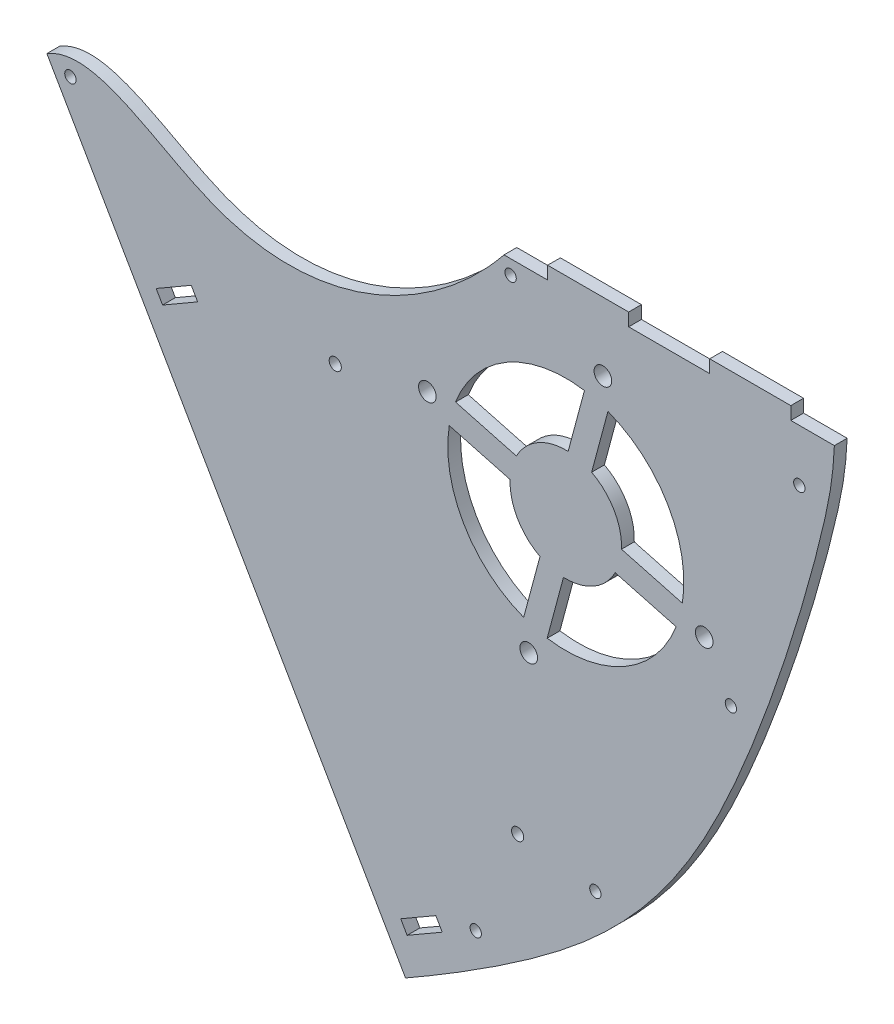
SolidWorks part; units mm, degrees
ref_plane "Front Plane" through (0, 0, 0) normal (0, 0, 1) x (1, 0, 0)
ref_plane "Top Plane" through (0, 0, 0) normal (0, 1, 0) x (1, 0, 0)
ref_plane "Right Plane" through (0, 0, 0) normal (1, 0, 0) x (0, 0, -1)
sketch "Sketch1" plane through (0, 0, 0) normal (0, 0, 1) x (1, 0, 0)
  line L0 (-241.6982, -23.3423) -> (-182.9843, -125.0377)
  line L1 (-213.036, -79.2761) -> (-94.3165, -10.7334) construction
  line L2 (-128.9095, -9.9573) -> (-47.4019, -9.9573)
  line L3 (-182.9843, -125.0377) -> (-153.2062, -176.6149)
  line L4 (-208.8162, -60.2955) -> (-150.0662, -162.0535) construction
  line L5 (-151.5313, -162.8993) -> (-146.1742, -159.8064) construction
  line L6 (-118.1557, -9.9573) -> (-98.1557, -9.9573)
  line L7 (-206.0711, -55.0502) -> (-214.7314, -60.0502)
  line L8 (-206.0711, -55.0502) -> (-204.4861, -57.7955)
  line L9 (-204.4861, -57.7955) -> (-213.1464, -62.7955)
  line L10 (-214.7314, -60.0502) -> (-213.1464, -62.7955)
  line L11 (-206.0711, -55.0502) -> (-213.1464, -62.7955) construction
  line L12 (-204.4861, -57.7955) -> (-214.7314, -60.0502) construction
  line L13 (-118.1557, -9.9573) -> (-118.1557, -6.7873)
  line L14 (-118.1557, -6.7873) -> (-98.1557, -6.7873)
  line L15 (-98.1557, -9.9573) -> (-98.1557, -6.7873)
  line L16 (-118.1557, -9.9573) -> (-98.1557, -6.7873) construction
  line L17 (-118.1557, -6.7873) -> (-98.1557, -9.9573) construction
  line L18 (-78.1557, -9.9573) -> (-58.1557, -9.9573)
  line L19 (-78.1557, -9.9573) -> (-78.1557, -6.7873)
  line L20 (-78.1557, -6.7873) -> (-58.1557, -6.7873)
  line L21 (-58.1557, -9.9573) -> (-58.1557, -6.7873)
  line L22 (-78.1557, -9.9573) -> (-58.1557, -6.7873) construction
  line L23 (-78.1557, -6.7873) -> (-58.1557, -9.9573) construction
  line L24 (-114.7432, -141.6597) -> (-155.5115, -165.1973) construction
  line L25 (-145.7361, -159.5535) -> (-152.8114, -167.2988) construction
  line L27 (-145.7361, -159.5535) -> (-154.3964, -164.5535)
  line L28 (-144.1511, -162.2988) -> (-152.8114, -167.2988)
  line L29 (-145.7361, -159.5535) -> (-144.1511, -162.2988)
  line L30 (-154.3964, -164.5535) -> (-152.8114, -167.2988)
  line L31 (-144.1511, -162.2988) -> (-154.3964, -164.5535) construction
  spline S0 degree 3 poles (-47.4019, -9.9573) (-47.8291, -14.2519) (-46.724, -19.9699) (-68.6824, -93.9596) (-98.4889, -144.1566) (-142.9712, -170.7541) (-153.2062, -176.6149) knots 0.137311 0.137311 0.137311 0.137311 0.404181 0.636361 0.837197 0.978117 0.978117 0.978117 0.978117
  spline S1 degree 3 poles (-241.6982, -23.3423) (-229.9179, -16.192) (-187.8178, -53.9735) (-145.5398, -30.6189) (-128.9095, -9.9573) knots 0 0 0 0 0.34889 1 1 1 1
  point P5 (-210.0721, -60.1842)
  point P18 (-209.6087, -58.9228)
  point P24 (-68.1557, -8.3723)
  point P27 (-108.1557, -8.3723)
  point P28 (-88.1557, -9.9573)
  point P38 (-149.7371, -164.6875)
  point P42 (-149.2737, -163.4261)
  dimension "D10" = 206.4057
  dimension "D1" = 3.17
  dimension "D2" = 10
  dimension "D3" = 10
  dimension "D4" = 10
  dimension "D5" = 20
  dimension "D6" = 3.17
  dimension "D7" = 5
  dimension "D8" = 3.17
  dimension "D9" = 10
extrude "Boss-Extrude1" add sketch "Sketch1" along normal blind 3.15 contours S1 L0 L3 S0 L2 L10 L7 L8 L9 | L2 L15 L14 L13 | L2 L21 L20 L19
sketch "Sketch2" plane through (0, 0, 0) normal (0, 0, 1) x (1, 0, 0)
  line L0 (-153.017, -94.8676) -> (-175.517, -55.8965)
  line L1 (-179.2053, -54.9082) -> (-196.5258, -64.9082)
  line L2 (-197.514, -68.5965) -> (-175.014, -107.5676)
  line L3 (-171.3258, -108.5559) -> (-154.0053, -98.5559)
  line L4 (-146.6291, -135.8318) -> (-151.1291, -128.0376)
  line L5 (-153.0908, -140.1398) -> (-146.8121, -136.5148)
  line L6 (-158.2738, -132.1626) -> (-153.7738, -139.9568)
  line L7 (-151.8121, -127.8546) -> (-158.0908, -131.4796)
  line L8 (-146.6291, -135.8318) -> (-151.1291, -128.0376)
  line L9 (-153.0908, -140.1398) -> (-146.8121, -136.5148)
  line L10 (-158.2738, -132.1626) -> (-153.7738, -139.9568)
  line L11 (-151.8121, -127.8546) -> (-158.0908, -131.4796)
  line L35 (-153.2768, -95.0176) -> (-175.7768, -56.0465) construction
  line L37 (-197.2542, -68.4465) -> (-174.7542, -107.4176) construction
  line L38 (-171.4758, -108.2961) -> (-154.1553, -98.2961) construction
  line L39 (-179.0553, -55.168) -> (-196.3758, -65.168) construction
  arc A0 (-175.517, -55.8965) -> (-179.2053, -54.9082) centre (-177.8553, -57.2465) ccw
  circle A1 centre (-145.4065, -140.7494) radius 3.5
  circle A2 centre (-145.4065, -140.7494) radius 3.5
  arc A3 (-196.5258, -64.9082) -> (-197.514, -68.5965) centre (-195.1758, -67.2465) ccw
  arc A4 (-154.1553, -98.2961) -> (-153.2768, -95.0176) centre (-155.3553, -96.2176) ccw construction
  arc A5 (-175.7768, -56.0465) -> (-179.0553, -55.168) centre (-177.8553, -57.2465) ccw construction
  arc A6 (-196.3758, -65.168) -> (-197.2542, -68.4465) centre (-195.1758, -67.2465) ccw construction
  arc A7 (-174.7542, -107.4176) -> (-171.4758, -108.2961) centre (-172.6758, -106.2176) ccw construction
  arc A8 (-175.014, -107.5676) -> (-171.3258, -108.5559) centre (-172.6758, -106.2176) ccw
  arc A9 (-154.0053, -98.5559) -> (-153.017, -94.8676) centre (-155.3553, -96.2176) ccw
  arc A10 (-146.8121, -136.5148) -> (-146.6291, -135.8318) centre (-147.0621, -136.0818) ccw
  arc A11 (-153.7738, -139.9568) -> (-153.0908, -140.1398) centre (-153.3408, -139.7068) ccw
  arc A12 (-158.0908, -131.4796) -> (-158.2738, -132.1626) centre (-157.8408, -131.9126) ccw
  arc A13 (-151.1291, -128.0376) -> (-151.8121, -127.8546) centre (-151.5621, -128.2876) ccw
  arc A14 (-146.8121, -136.5148) -> (-146.6291, -135.8318) centre (-147.0621, -136.0818) ccw
  arc A15 (-153.7738, -139.9568) -> (-153.0908, -140.1398) centre (-153.3408, -139.7068) ccw
  arc A16 (-158.0908, -131.4796) -> (-158.2738, -132.1626) centre (-157.8408, -131.9126) ccw
  arc A17 (-151.1291, -128.0376) -> (-151.8121, -127.8546) centre (-151.5621, -128.2876) ccw
  dimension "D1" = 0
  dimension "D2" = 0
  dimension "D3" = 0.3
extrude "Cut-Extrude2" [suppressed] cut sketch "Sketch2" along normal blind 10
sketch "Sketch3" plane through (0, 0, 3.15) normal (0, 0, 1) x (1, 0, 0)
  circle A0 centre (-170.5478, -54.0783) radius 1.5 construction
  circle A1 centre (-170.5478, -54.0783) radius 1.5
  circle A3 centre (-125.5478, -132.0206) radius 1.5
  circle A4 centre (-125.5478, -132.0206) radius 1.5
  dimension "D1" = 0
extrude "Cut-Extrude3" cut sketch "Sketch3" against normal blind 4
sketch "Sketch4" plane through (0, 0, 0) normal (0, 0, -1) x (-1, 0, 0)
  circle A1 centre (235.8922, -25.3985) radius 1.4
  circle A2 centre (235.8922, -25.3985) radius 1.4
  dimension "D1" = 0
extrude "Cut-Extrude4" cut sketch "Sketch4" against normal through all
sketch "Sketch5" plane through (0, 0, 0) normal (0, 0, -1) x (-1, 0, 0)
  circle A0 centre (127.2847, -13.4927) radius 1.4 construction
  circle A1 centre (127.2847, -13.4927) radius 1.4
extrude "Cut-Extrude5" cut sketch "Sketch5" against normal blind 10
sketch "SidePlateStand-LaserCutLayout" [suppressed] plane through (0, 0, 3.15) normal (0, 0, 1) x (1, 0, 0)
  line L4 (-154.3964, -164.5535) -> (-152.8114, -167.2988)
  line L5 (-145.7361, -159.5535) -> (-154.3964, -164.5535)
  line L6 (-144.1511, -162.2988) -> (-145.7361, -159.5535)
  line L7 (-152.8114, -167.2988) -> (-144.1511, -162.2988)
  line L8 (-154.3964, -164.5535) -> (-152.8114, -167.2988)
  line L9 (-145.7361, -159.5535) -> (-154.3964, -164.5535)
  line L10 (-241.6982, -23.3423) -> (-153.2062, -176.6149)
  line L11 (-47.4019, -9.9573) -> (-58.1557, -9.9573)
  line L12 (-58.1557, -9.9573) -> (-58.1557, -6.7873)
  line L13 (-58.1557, -6.7873) -> (-78.1557, -6.7873)
  line L14 (-78.1557, -6.7873) -> (-78.1557, -9.9573)
  line L15 (-78.1557, -9.9573) -> (-98.1557, -9.9573)
  line L16 (-98.1557, -9.9573) -> (-98.1557, -6.7873)
  line L17 (-98.1557, -6.7873) -> (-118.1557, -6.7873)
  line L18 (-118.1557, -6.7873) -> (-118.1557, -9.9573)
  line L19 (-118.1557, -9.9573) -> (-128.9095, -9.9573)
  line L20 (-241.6982, -23.3423) -> (-153.2062, -176.6149)
  line L21 (-47.4019, -9.9573) -> (-58.1557, -9.9573)
  line L22 (-58.1557, -9.9573) -> (-58.1557, -6.7873)
  line L23 (-58.1557, -6.7873) -> (-78.1557, -6.7873)
  line L24 (-78.1557, -6.7873) -> (-78.1557, -9.9573)
  line L25 (-78.1557, -9.9573) -> (-98.1557, -9.9573)
  line L26 (-98.1557, -9.9573) -> (-98.1557, -6.7873)
  line L27 (-98.1557, -6.7873) -> (-118.1557, -6.7873)
  line L28 (-118.1557, -6.7873) -> (-118.1557, -9.9573)
  line L29 (-118.1557, -9.9573) -> (-128.9095, -9.9573)
  line L30 (-144.1511, -162.2988) -> (-145.7361, -159.5535)
  line L31 (-152.8114, -167.2988) -> (-144.1511, -162.2988)
  line L32 (-214.7314, -60.0502) -> (-213.1464, -62.7955)
  line L33 (-206.0711, -55.0502) -> (-214.7314, -60.0502)
  line L34 (-204.4861, -57.7955) -> (-206.0711, -55.0502)
  line L35 (-213.1464, -62.7955) -> (-204.4861, -57.7955)
  line L36 (-214.7314, -60.0502) -> (-213.1464, -62.7955)
  line L37 (-206.0711, -55.0502) -> (-214.7314, -60.0502)
  line L38 (-204.4861, -57.7955) -> (-206.0711, -55.0502)
  line L39 (-213.1464, -62.7955) -> (-204.4861, -57.7955)
  line L40 (-151.8121, -127.8546) -> (-158.0908, -131.4796)
  line L41 (-146.6291, -135.8318) -> (-151.1291, -128.0376)
  line L42 (-153.0908, -140.1398) -> (-146.8121, -136.5148)
  line L43 (-158.2738, -132.1626) -> (-153.7738, -139.9568)
  line L44 (-151.8121, -127.8546) -> (-158.0908, -131.4796)
  line L45 (-146.6291, -135.8318) -> (-151.1291, -128.0376)
  line L46 (-153.0908, -140.1398) -> (-146.8121, -136.5148)
  line L47 (-158.2738, -132.1626) -> (-153.7738, -139.9568)
  line L48 (-153.017, -94.8676) -> (-175.517, -55.8965)
  line L49 (-171.3258, -108.5559) -> (-154.0053, -98.5559)
  line L50 (-197.514, -68.5965) -> (-175.014, -107.5676)
  line L51 (-179.2053, -54.9082) -> (-196.5258, -64.9082)
  line L52 (-153.017, -94.8676) -> (-175.517, -55.8965)
  line L53 (-171.3258, -108.5559) -> (-154.0053, -98.5559)
  line L54 (-197.514, -68.5965) -> (-175.014, -107.5676)
  line L55 (-179.2053, -54.9082) -> (-196.5258, -64.9082)
  circle A1 centre (-145.4065, -140.7494) radius 3.5
  circle A2 centre (-145.4065, -140.7494) radius 3.5
  circle A3 centre (-235.8922, -25.3985) radius 1.4
  circle A4 centre (-235.8922, -25.3985) radius 1.4
  circle A5 centre (-127.2847, -13.4927) radius 1.4
  arc A6 (-151.1291, -128.0376) -> (-151.8121, -127.8546) centre (-151.5621, -128.2876) ccw
  arc A7 (-146.8121, -136.5148) -> (-146.6291, -135.8318) centre (-147.0621, -136.0818) ccw
  arc A8 (-153.7738, -139.9568) -> (-153.0908, -140.1398) centre (-153.3408, -139.7068) ccw
  arc A9 (-158.0908, -131.4796) -> (-158.2738, -132.1626) centre (-157.8408, -131.9126) ccw
  arc A10 (-151.1291, -128.0376) -> (-151.8121, -127.8546) centre (-151.5621, -128.2876) ccw
  arc A11 (-146.8121, -136.5148) -> (-146.6291, -135.8318) centre (-147.0621, -136.0818) ccw
  arc A12 (-153.7738, -139.9568) -> (-153.0908, -140.1398) centre (-153.3408, -139.7068) ccw
  arc A13 (-158.0908, -131.4796) -> (-158.2738, -132.1626) centre (-157.8408, -131.9126) ccw
  arc A14 (-154.0053, -98.5559) -> (-153.017, -94.8676) centre (-155.3553, -96.2176) ccw
  arc A15 (-175.014, -107.5676) -> (-171.3258, -108.5559) centre (-172.6758, -106.2176) ccw
  arc A16 (-196.5258, -64.9082) -> (-197.514, -68.5965) centre (-195.1758, -67.2465) ccw
  arc A17 (-175.517, -55.8965) -> (-179.2053, -54.9082) centre (-177.8553, -57.2465) ccw
  arc A18 (-154.0053, -98.5559) -> (-153.017, -94.8676) centre (-155.3553, -96.2176) ccw
  arc A19 (-175.014, -107.5676) -> (-171.3258, -108.5559) centre (-172.6758, -106.2176) ccw
  arc A20 (-196.5258, -64.9082) -> (-197.514, -68.5965) centre (-195.1758, -67.2465) ccw
  arc A21 (-175.517, -55.8965) -> (-179.2053, -54.9082) centre (-177.8553, -57.2465) ccw
  circle A22 centre (-127.2847, -13.4927) radius 1.4
  spline S2 degree 3 poles (-2267.8116, -2087.8832) (141.433, 821.0921) (-106.9978, -507.9229) (-349.4539, 215.3672) (-44.3825, -3015.1336) knots -3.369969 -3.369969 -3.369969 -3.369969 0.65111 2.42395 2.42395 2.42395 2.42395 only from (-128.9095, -9.9573) to (-241.6982, -23.3423)
  spline S3 degree 3 poles (2612.6178, 984.7464) (-488.0662, -275.5146) (-139.2313, -212.7707) (-68.6824, -93.9596) (0.2312, 138.2476) (-205.2125, -403.0137) (1080.8844, 2769.6644) knots -0.647202 -0.647202 -0.647202 -0.647202 0.278231 0.479068 0.711248 2.474733 2.474733 2.474733 2.474733 only from (-153.2062, -176.6149) to (-47.4019, -9.9573)
  spline S4 degree 3 poles (-128.9095, -9.9573) (-145.5398, -30.6189) (-187.8178, -53.9735) (-229.9179, -16.192) (-241.6982, -23.3423) knots 0 0 0 0 0.65111 1 1 1 1
  spline S5 degree 3 poles (-153.2062, -176.6149) (-142.9712, -170.7541) (-98.4889, -144.1566) (-68.6824, -93.9596) (-46.724, -19.9699) (-47.8291, -14.2519) (-47.4019, -9.9573) knots 0.137311 0.137311 0.137311 0.137311 0.278231 0.479068 0.711248 0.978117 0.978117 0.978117 0.978117
  dimension "D1" = 0
  dimension "D2" = 0
  dimension "D3" = 0
  dimension "D4" = 0
  dimension "D5" = 0
  dimension "D6" = 0
  dimension "D7" = 0
  dimension "D8" = 0
sketch "Sketch8" plane through (0, 0, 0) normal (0, 0, -1) x (-1, 0, 0)
  circle A4 centre (56.0495, -22.79) radius 1.4
  circle A5 centre (72.9293, -78.3323) radius 1.4
  circle A6 centre (106.3655, -134.6753) radius 1.4
  circle A7 centre (135.8793, -157.853) radius 1.4
  circle A8 centre (135.8793, -157.853) radius 1.4 construction
  circle A9 centre (106.3655, -134.6753) radius 1.4 construction
  circle A10 centre (72.9293, -78.3323) radius 1.4 construction
  circle A11 centre (56.0495, -22.79) radius 1.4 construction
extrude "Cut-Extrude6" cut sketch "Sketch8" against normal blind 3.15
sketch "Sketch9" plane through (0, 0, 0) normal (0, 0, -1) x (-1, 0, 0)
  line L0 (241.6982, -23.3423) -> (153.2062, -176.6149) construction
  line L1 (125.4675, -68.6574) -> (119.4053, -65.1574)
  line L2 (126.1995, -71.3895) -> (119.6995, -82.6478)
  line L3 (116.9675, -83.3799) -> (110.9053, -79.8799)
  line L4 (116.6732, -65.8895) -> (110.1732, -77.1478)
  line L5 (127.1995, -69.6574) -> (109.1732, -78.8799) construction
  line L6 (118.6995, -84.3799) -> (117.6732, -64.1574) construction
  arc A0 (126.1995, -71.3895) -> (125.4675, -68.6574) centre (124.4675, -70.3895) ccw
  arc A1 (116.9675, -83.3799) -> (119.6995, -82.6478) centre (117.9675, -81.6478) ccw
  arc A2 (110.9053, -79.8799) -> (110.1732, -77.1478) centre (111.9053, -78.1478) cw
  arc A3 (116.6732, -65.8895) -> (119.4053, -65.1574) centre (118.4053, -66.8895) cw
  point P4 (118.1864, -74.2687)
  dimension "D3" = 2
  dimension "D1" = 17
  dimension "D2" = 11
extrude "Cut-Extrude8" [suppressed] cut sketch "Sketch9" against normal blind 10
sketch "Laser Cut Trace" plane through (0, 0, 3.15) normal (0, 0, 1) x (1, 0, 0)
  line L8 (-58.1557, -9.9573) -> (-47.4019, -9.9573) construction
  line L9 (-58.1557, -9.9573) -> (-58.1557, -6.7873) construction
  line L10 (-78.1557, -6.7873) -> (-58.1557, -6.7873) construction
  line L11 (-78.1557, -9.9573) -> (-78.1557, -6.7873) construction
  line L12 (-214.7314, -60.0502) -> (-213.1464, -62.7955)
  line L13 (-206.0711, -55.0502) -> (-214.7314, -60.0502)
  line L14 (-204.4861, -57.7955) -> (-206.0711, -55.0502)
  line L15 (-213.1464, -62.7955) -> (-204.4861, -57.7955)
  line L16 (-214.7314, -60.0502) -> (-213.1464, -62.7955)
  line L17 (-206.0711, -55.0502) -> (-214.7314, -60.0502)
  line L18 (-204.4861, -57.7955) -> (-206.0711, -55.0502)
  line L19 (-213.1464, -62.7955) -> (-204.4861, -57.7955)
  line L20 (-154.3964, -164.5535) -> (-152.8114, -167.2988)
  line L21 (-145.7361, -159.5535) -> (-154.3964, -164.5535)
  line L22 (-144.1511, -162.2988) -> (-145.7361, -159.5535)
  line L23 (-152.8114, -167.2988) -> (-144.1511, -162.2988)
  line L24 (-154.3964, -164.5535) -> (-152.8114, -167.2988)
  line L25 (-145.7361, -159.5535) -> (-154.3964, -164.5535)
  line L26 (-144.1511, -162.2988) -> (-145.7361, -159.5535)
  line L27 (-152.8114, -167.2988) -> (-144.1511, -162.2988)
  line L28 (-98.1557, -9.9573) -> (-78.1557, -9.9573) construction
  line L29 (-118.1557, -6.7873) -> (-98.1557, -6.7873) construction
  line L30 (-118.1557, -9.9573) -> (-118.1557, -6.7873) construction
  line L31 (-128.9095, -9.9573) -> (-118.1557, -9.9573) construction
  line L32 (-241.6982, -23.3423) -> (-153.2062, -176.6149) construction
  line L33 (-58.1557, -9.9573) -> (-47.4019, -9.9573)
  line L34 (-58.1557, -9.9573) -> (-58.1557, -6.7873)
  line L35 (-78.1557, -6.7873) -> (-58.1557, -6.7873)
  line L36 (-78.1557, -9.9573) -> (-78.1557, -6.7873)
  line L37 (-98.1557, -9.9573) -> (-78.1557, -9.9573)
  line L38 (-118.1557, -6.7873) -> (-98.1557, -6.7873)
  line L39 (-118.1557, -9.9573) -> (-118.1557, -6.7873)
  line L40 (-128.9095, -9.9573) -> (-118.1557, -9.9573)
  line L41 (-241.6982, -23.3423) -> (-153.2062, -176.6149)
  circle A0 centre (-56.0495, -22.79) radius 1.4 construction
  circle A1 centre (-72.9293, -78.3323) radius 1.4 construction
  circle A2 centre (-106.3655, -134.6753) radius 1.4 construction
  circle A3 centre (-135.8793, -157.853) radius 1.4 construction
  circle A4 centre (-56.0495, -22.79) radius 1.4
  circle A5 centre (-170.5478, -54.0783) radius 1.5
  circle A6 centre (-170.5478, -54.0783) radius 1.5
  circle A7 centre (-125.5478, -132.0206) radius 1.5
  circle A8 centre (-125.5478, -132.0206) radius 1.5
  circle A9 centre (-235.8922, -25.3985) radius 1.4
  circle A10 centre (-235.8922, -25.3985) radius 1.4
  circle A11 centre (-127.2847, -13.4927) radius 1.4
  circle A12 centre (-127.2847, -13.4927) radius 1.4
  circle A13 centre (-72.9293, -78.3323) radius 1.4
  circle A14 centre (-106.3655, -134.6753) radius 1.4
  circle A15 centre (-135.8793, -157.853) radius 1.4
  spline S0 degree 3 poles (704.9048, 1843.1432) (-167.5252, -304.1648) (-5.9039, 117.5752) (-68.6824, -93.9596) (-133.806, -203.634) (-425.8521, -263.5673) (1686.9018, 606.2528) knots -1.163759 -1.163759 -1.163759 -1.163759 0.404181 0.636361 0.837197 1.658164 1.658164 1.658164 1.658164 only from (-47.4019, -9.9573) to (-153.2062, -176.6149) construction
  spline S1 degree 3 poles (-136.2786, -2019.5522) (-332.1345, 166.3389) (-114.9569, -415.3991) (107.006, 646.6359) (-1620.3597, -1325.8317) knots -1.217103 -1.217103 -1.217103 -1.217103 0.34889 3.96818 3.96818 3.96818 3.96818 only from (-241.6982, -23.3423) to (-128.9095, -9.9573) construction
  spline S2 degree 3 poles (-47.4019, -9.9573) (-47.8291, -14.2519) (-46.724, -19.9699) (-68.6824, -93.9596) (-98.4889, -144.1566) (-142.9712, -170.7541) (-153.2062, -176.6149) knots 0.137311 0.137311 0.137311 0.137311 0.404181 0.636361 0.837197 0.978117 0.978117 0.978117 0.978117
  spline S3 degree 3 poles (-241.6982, -23.3423) (-229.9179, -16.192) (-187.8178, -53.9735) (-145.5398, -30.6189) (-128.9095, -9.9573) knots 0 0 0 0 0.34889 1 1 1 1
  dimension "D1" = 0
  dimension "D2" = 0
  dimension "D3" = 0
  dimension "D4" = 0
  dimension "D5" = 0
  dimension "D6" = 0
sketch "Sketch10" plane through (0, 0, 0) normal (0, 0, -1) x (-1, 0, 0)
  line L0 (88.4386, -43.2193) -> (101.7538, -50.9068) construction
  line L1 (122.8123, -91.9324) -> (79.511, -66.9324) construction
  line L2 (122.8123, -91.9324) -> (147.8123, -48.6311) construction
  line L3 (147.8123, -48.6311) -> (104.511, -23.6311) construction
  line L4 (79.511, -66.9324) -> (104.511, -23.6311) construction
  line L5 (79.511, -66.9324) -> (100.3801, -61.3405) construction
  line L6 (122.8123, -91.9324) -> (117.2204, -71.0632) construction
  line L7 (92.011, -45.2818) -> (101.7538, -50.9068) construction
  line L8 (98.1557, -9.9573) -> (98.1557, -6.7873) construction
  line L9 (106.7866, -69.6896) -> (99.0991, -83.0047) construction
  line L10 (241.6982, -23.3423) -> (153.2062, -176.6149) construction
  line L11 (124.0574, -84.9883) -> (120.0324, -69.9668)
  line L15 (86.4551, -68.1775) -> (101.4766, -64.1526)
  line L17 (84.9022, -62.382) -> (99.9237, -58.357)
  line L18 (125.71, -91.1559) -> (107.4088, -22.8547) construction
  line L19 (118.2618, -86.5412) -> (114.2369, -71.5197)
  line L20 (107.2908, -45.5967) -> (103.2658, -30.5753)
  line L21 (127.3996, -57.2065) -> (142.421, -53.1815)
  line L22 (125.8467, -51.411) -> (140.8681, -47.386)
  line L23 (113.0864, -44.0438) -> (109.0614, -29.0224)
  line L24 (126.9431, -54.223) -> (147.8123, -48.6311) construction
  line L25 (118.1557, -6.7873) -> (98.1557, -6.7873) construction
  line L26 (72.9293, -78.3323) -> (77.2208, -70.8991)
  line L27 (110.1029, -44.5003) -> (104.511, -23.6311) construction
  line L28 (122.8123, -91.9324) -> (104.511, -23.6311) construction
  line L29 (120.5366, -45.8739) -> (126.1616, -36.1311) construction
  line L30 (125.5695, -64.6568) -> (135.3123, -70.2818) construction
  circle A0 centre (79.511, -66.9324) radius 2.175
  circle A1 centre (122.8123, -91.9324) radius 2.175
  circle A2 centre (147.8123, -48.6311) radius 2.175
  circle A3 centre (104.511, -23.6311) radius 2.175
  circle A4 centre (113.6616, -57.7818) radius 29.125
  arc A5 (101.4766, -64.1526) -> (114.2369, -71.5197) centre (113.6616, -57.7818) ccw
  arc A6 (120.0324, -69.9668) -> (127.3996, -57.2065) centre (113.6616, -57.7818) ccw
  arc A7 (125.8467, -51.411) -> (113.0864, -44.0438) centre (113.6616, -57.7818) ccw
  arc A8 (107.2908, -45.5967) -> (99.9237, -58.357) centre (113.6616, -57.7818) ccw
  point P29 (114.3421, -58.1747)
  point P156 (104.511, -41.9324)
other "AlignGroup1"
other "AlignGroup2" parameters "D2"=5.3339, "D3"=57.9132, "D5"=30.5779, "D4"=13.75, "D1"=53.0162, "D6"=4.6002, "D7"=6.3708, "D8"=9.1506, "D9"=10.3958, "D10"=12.185, "D11"=13.738, "D12"=27.2065, "D13"=28.7594, "D14"=34.1506, "D15"=0.5752, "D16"=4.6002, "D17"=6.3708, "D18"=9.1506, "D19"=10.3958, "D20"=12.185, "D21"=13.738, "D22"=27.2065, "D23"=28.7594, "D24"=34.1506
extrude "Cut-Extrude9" cut sketch "Sketch10" against normal blind 10 contours A5 L15 A4 L19 | A8 L20 A4 L17 | A7 L22 A4 L23 | A6 L11 A4 L21 | A2 | A3 | A0 | A1
